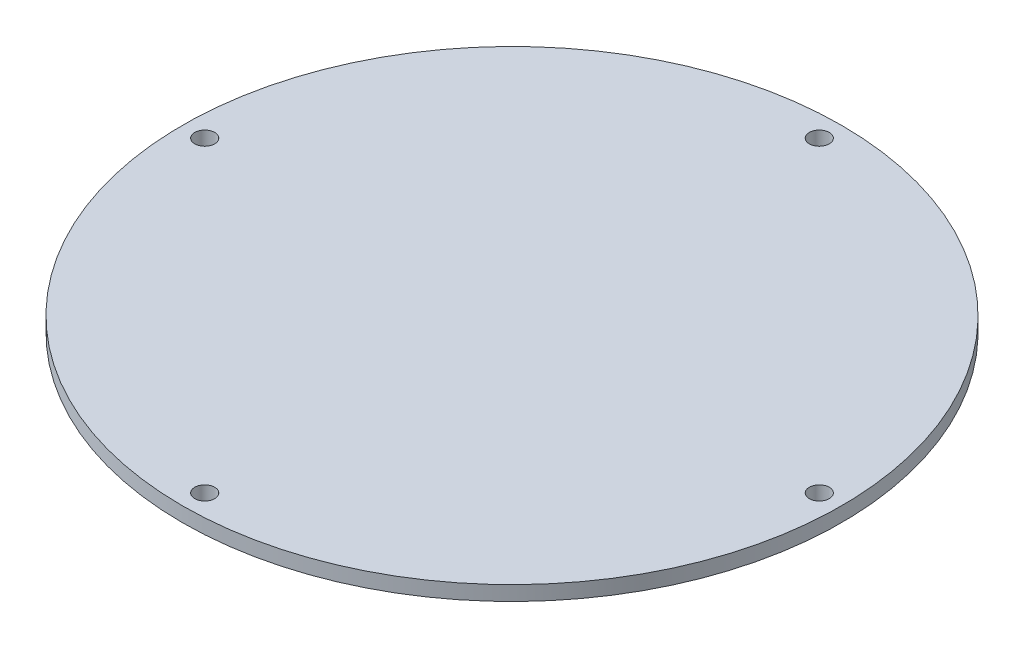
SolidWorks part; units mm, degrees
ref_plane "Front Plane" through (0, 0, 0) normal (0, 0, 1) x (1, 0, 0)
ref_plane "Top Plane" through (0, 0, 0) normal (0, 1, 0) x (1, 0, 0)
ref_plane "Right Plane" through (0, 0, 0) normal (1, 0, 0) x (0, 0, -1)
sketch "Sketch1" plane through (0, 0, 0) normal (0, 1, 0) x (1, 0, 0)
  circle A0 centre (0, 0) radius 57.15
  dimension "D1" = 114.3
extrude "Boss-Extrude1" add sketch "Sketch1" along normal blind 2.54
sketch "Sketch3" plane through (0, 2.54, 0) normal (0, 1, 0) x (1, 0, 0)
  point P0 (-53.2863, 0)
  dimension "D1" = 53.2863
hole_wizard "#8-32 Tapped Hole1" positions "Sketch3" profile "Sketch4" tap size "#8-32" standard "ANSI Inch" end condition through all
sketch "Sketch4" plane through (-53.2863, 2.54, 0) normal (1, 0, 0) x (0, 0, 1)
  line L0 (0, 0) -> (0, 2.54)
  line L1 (0, 2.54) -> (1.7272, 2.54)
  line L2 (1.7272, 2.54) -> (1.7272, 0)
  line L5 (1.7272, 0) -> (0, 0)
  line L11 (0, -6.35) -> (0, 107.95) construction
  dimension "Thru Tap Drill Dia." = 3.4544
  dimension "Thru Tap Drill Depth" = 2.54
cosmetic thread "Hole Thread1"
pattern_circular "CirPattern1" count 4 over 360 about axis through (0, 0, 0) along (0, 1, 0) of "#8-32 Tapped Hole1"
cosmetic thread "Hole Thread2"
cosmetic thread "Hole Thread3"
cosmetic thread "Hole Thread4"
